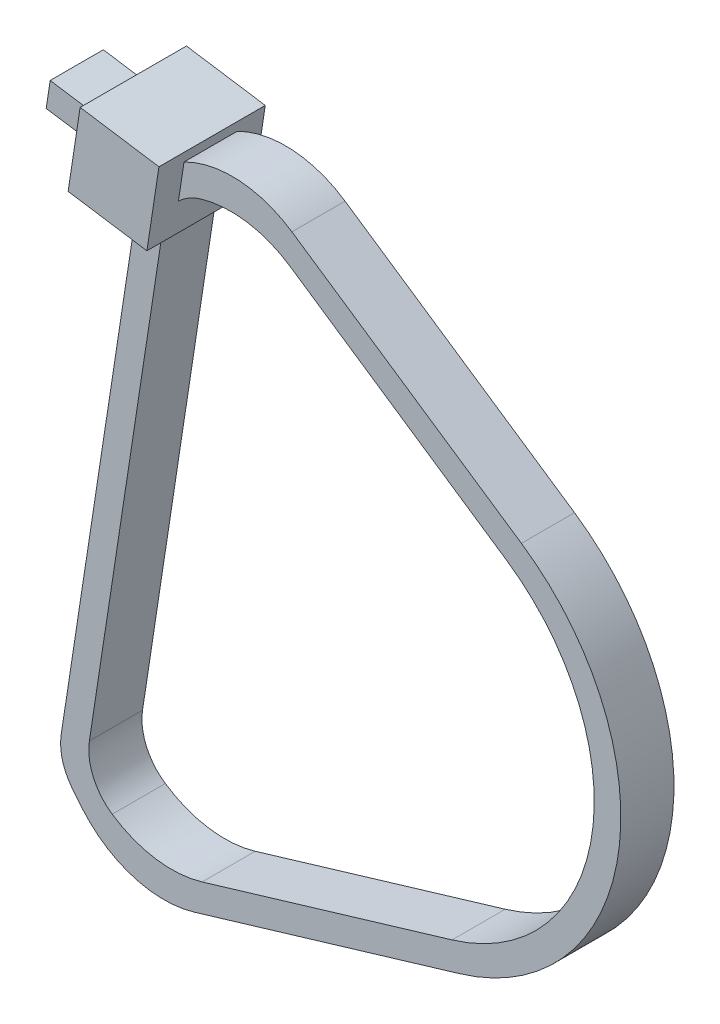
SolidWorks part; units mm, degrees
ref_plane "Front Plane" through (0, 0, 0) normal (0, 0, 1) x (1, 0, 0)
ref_plane "Top Plane" through (0, 0, 0) normal (0, 1, 0) x (1, 0, 0)
ref_plane "Right Plane" through (0, 0, 0) normal (1, 0, 0) x (0, 0, -1)
sketch "Sketch1" plane through (0, 0, 0) normal (0, 0, 1) x (1, 0, 0)
  line L0 (-7.2571, -9.9999) -> (2.1499, -7.1853)
  line L1 (2.4365, -8.1433) -> (-7.5484, -11.1309)
  line L2 (0, 0) -> (-9.6189, 1.4705) construction
  line L3 (-8.8066, 6.7838) -> (-10.4311, -3.8428) construction
  line L4 (-9.6189, 1.4705) -> (15.1759, -2.32) construction
  line L5 (-9.6189, 1.4705) -> (-17.9253, 2.7403) construction
  line L6 (4.7582, 7.0434) -> (-3.878, 12.8777)
  line L7 (-3.938, 11.7114) -> (4.1984, 6.2148)
  line L8 (-11.4996, -7.5233) -> (-8.7266, 10.6154)
  line L9 (-12.5596, -7.8398) -> (-9.6437, 11.2341)
  line L10 (-14.9081, -33.1275) -> (-10.3745, -3.4721) construction
  line L11 (-10.3745, -3.4721) -> (-8.1077, 11.3556) construction
  arc A0 (-12.5596, -7.8398) -> (-12.1677, -9.3616) centre (-10.5826, -8.142) ccw
  arc A1 (-8.2726, 12.9327) -> (-8.815, 12.5693) centre (0, 0) ccw
  circle A2 centre (0, 0) radius 7.5 construction
  arc A3 (2.4365, -8.1433) -> (4.7582, 7.0434) centre (0, 0) ccw
  arc A4 (-7.5484, -11.1309) -> (-11.7587, -9.8704) centre (-8.695, -7.2987) cw
  arc A5 (-7.2571, -9.9999) -> (-10.6414, -9.4833) centre (-8.4037, -6.1678) cw
  arc A6 (-3.938, 11.7114) -> (-7.3221, 12.2295) centre (-6.1772, 8.3968) ccw
  arc A7 (-3.878, 12.8777) -> (-8.2726, 12.9327) centre (-6.1172, 9.5631) ccw
  arc A8 (2.1499, -7.1853) -> (4.1984, 6.2148) centre (0, 0) ccw
  arc A9 (-12.1677, -9.3616) -> (-11.7587, -9.8704) centre (0, 0) ccw
  arc A10 (-11.4996, -7.5233) -> (-10.6414, -9.4833) centre (-9.5226, -7.8256) ccw
  arc A11 (-8.7266, 10.6154) -> (-7.3221, 12.2295) centre (-6.7496, 10.3132) cw
  arc A12 (-9.6437, 11.2341) -> (-8.815, 12.5693) centre (-7.6666, 10.9319) cw
  point P32 (-12.6835, -8.65)
  point P35 (-11.6497, -8.5052)
  point P38 (-8.5765, 11.5973)
  dimension "D1" = 2
  dimension "D3" = 1
  dimension "D4" = 4
  dimension "D5" = 2.1499
  dimension "D6" = 1
  dimension "D7" = 0.5
  dimension "D8" = 10.4242
  dimension "D2" = 1
  dimension "D9" = 11.3523
extrude "Boss-Extrude1" add sketch "Sketch1" along normal blind 2 from offset 1.25 offset against normal yes
sketch "Sketch2" plane through (0, 0, 0.75) normal (0, 0, 1) x (1, 0, 0)
  line L1 (-8.3349, 10.5308) -> (-11.3005, 10.9841)
  line L2 (-8.3349, 10.5308) -> (-7.8816, 13.4963)
  line L3 (-7.8816, 13.4963) -> (-10.8471, 13.9497)
  line L4 (-11.3005, 10.9841) -> (-10.8471, 13.9497)
  line L5 (-8.3349, 10.5308) -> (-10.8471, 13.9497) construction
  line L6 (-7.8816, 13.4963) -> (-11.3005, 10.9841) construction
  line L9 (-8.1077, 11.3556) -> (-2.8185, 45.9537) construction
  line L10 (-8.7266, 10.6154) -> (-11.4996, -7.5233) construction
  line L11 (-9.6437, 11.2341) -> (-12.5596, -7.8398) construction
  point P0 (-9.591, 12.2402)
  point P7 (-10.1131, 1.5461)
  point P10 (-11.1016, 1.6972)
  dimension "D1" = 3
  dimension "D2" = 0.1
  dimension "D3" = 3
  dimension "D4" = 12.2402
extrude "Boss-Extrude2" add sketch "Sketch2" along normal blind 1 and the other way blind 3
sketch "Sketch3" plane through (-12.6833, 1.939, 0) normal (-0.9885, 0.1511, 0) x (0, 0, 1)
  line L0 (0.75, 11.7741) -> (0.75, 10.3747) construction
  line L1 (-1.25, 10.1502) -> (0.75, 10.1502)
  line L2 (-1.25, 10.1502) -> (-1.25, 11.1502)
  line L3 (-1.25, 11.1502) -> (0.75, 11.1502)
  line L4 (0.75, 10.1502) -> (0.75, 11.1502)
  line L5 (-1.25, 10.1502) -> (0.75, 11.1502) construction
  line L6 (-1.25, 11.1502) -> (0.75, 10.1502) construction
  line L7 (-1.25, 9.1502) -> (-1.25, -9.6477) construction
  line L8 (-2.25, 9.1502) -> (1.75, 9.1502) construction
  point P0 (-0.25, 10.6502)
  dimension "D1" = 1
  dimension "D2" = 1.5
extrude "Boss-Extrude3" add sketch "Sketch3" along normal blind 2
